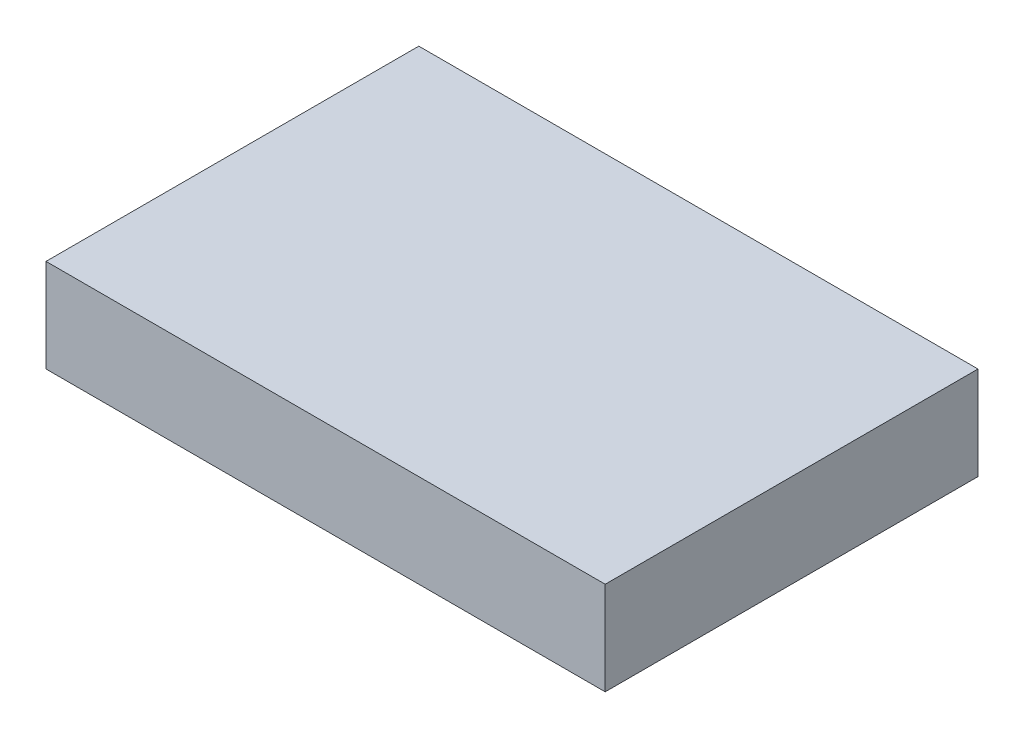
SolidWorks part; units mm, degrees
material "Oak"
ref_plane "Front Plane" through (0, 0, 0) normal (0, 0, 1) x (1, 0, 0)
ref_plane "Top Plane" through (0, 0, 0) normal (0, 1, 0) x (1, 0, 0)
ref_plane "Right Plane" through (0, 0, 0) normal (1, 0, 0) x (0, 0, -1)
sketch "Sketch1" plane through (0, 0, 0) normal (0, 1, 0) x (1, 0, 0)
  line L1 (-38.1, -25.4) -> (38.1, -25.4)
  line L2 (-38.1, -25.4) -> (-38.1, 25.4)
  line L3 (-38.1, 25.4) -> (38.1, 25.4)
  line L4 (38.1, -25.4) -> (38.1, 25.4)
  line L5 (-38.1, -25.4) -> (38.1, 25.4) construction
  line L6 (-38.1, 25.4) -> (38.1, -25.4) construction
  point P0 (0, 0)
  dimension "D1" = 50.8
  dimension "D2" = 76.2
extrude "Boss-Extrude1" add sketch "Sketch1" along normal mid plane 12.7
